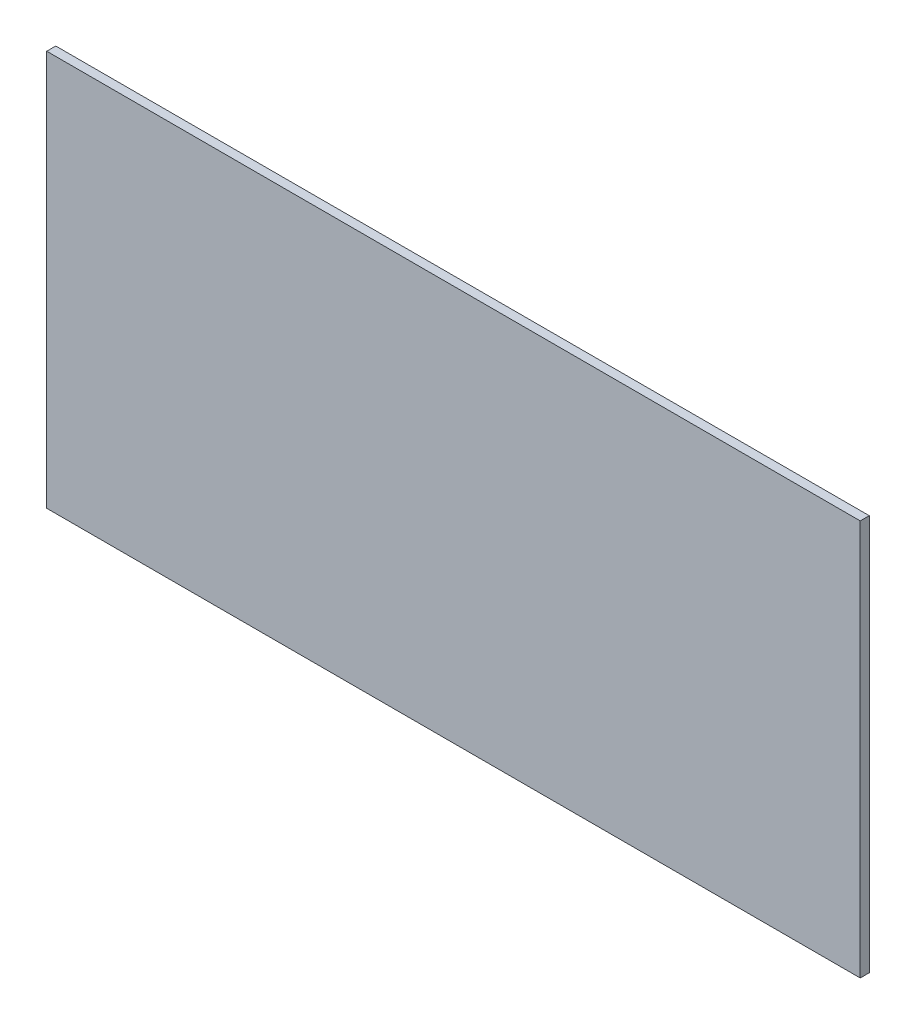
SolidWorks part; units mm, degrees
ref_plane "Front Plane" through (0, 0, 0) normal (0, 0, 1) x (1, 0, 0)
ref_plane "Top Plane" through (0, 0, 0) normal (0, 1, 0) x (1, 0, 0)
ref_plane "Right Plane" through (0, 0, 0) normal (1, 0, 0) x (0, 0, -1)
sketch "Sketch1" plane through (0, 0, 0) normal (0, 0, 1) x (1, 0, 0)
  line L0 (0, 0) -> (0, 69.5588)
  line L5 (0, 69.5588) -> (142.9412, 69.5588)
  line L6 (142.9412, 69.5588) -> (142.9412, 0)
  line L7 (142.9412, 0) -> (0, 0)
extrude "Boss-Extrude1" add sketch "Sketch1" along normal blind 1.5875
